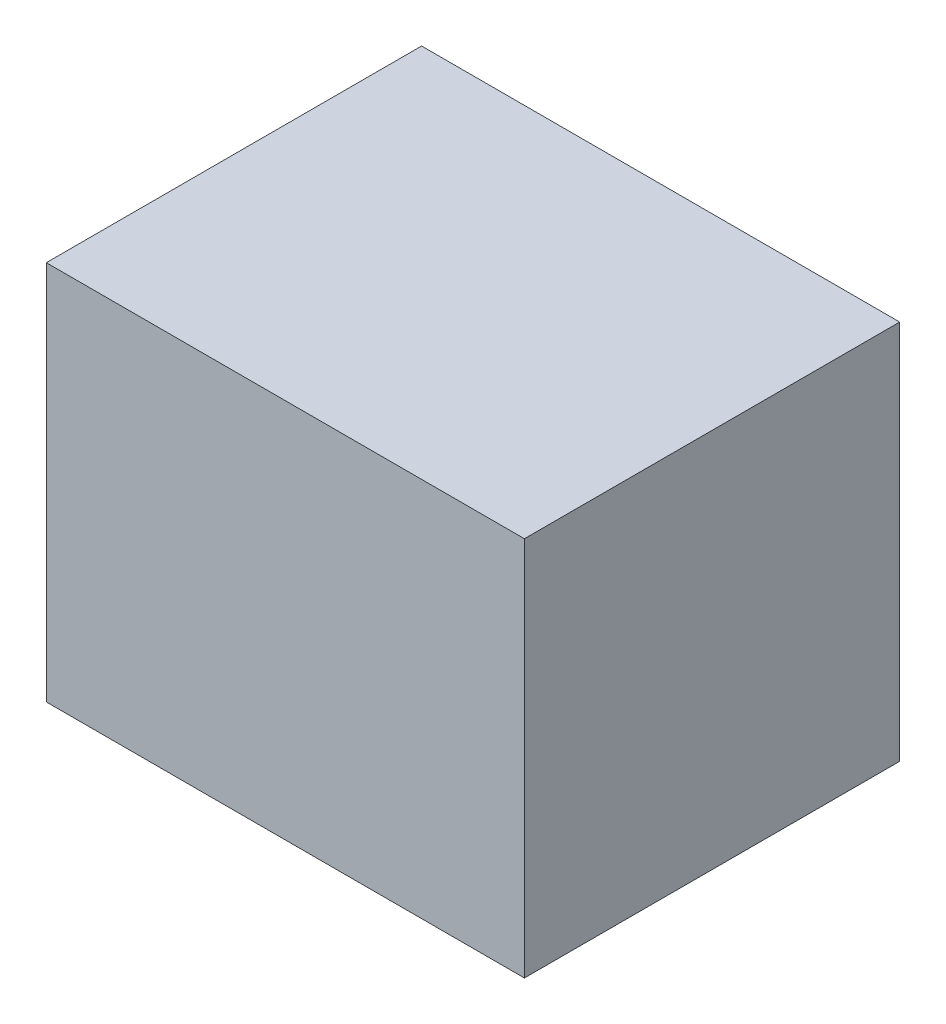
SolidWorks part; units mm, degrees
ref_plane "Front Plane" through (0, 0, 0) normal (0, 0, 1) x (1, 0, 0)
ref_plane "Top Plane" through (0, 0, 0) normal (0, 1, 0) x (1, 0, 0)
ref_plane "Right Plane" through (0, 0, 0) normal (1, 0, 0) x (0, 0, -1)
sketch "Sketch1" plane through (0, 0, 0) normal (0, 0, 1) x (1, 0, 0)
  line L1 (-46.5, -37) -> (46.5, -37)
  line L2 (-46.5, -37) -> (-46.5, 37)
  line L3 (-46.5, 37) -> (46.5, 37)
  line L4 (46.5, -37) -> (46.5, 37)
  line L5 (-46.5, -37) -> (46.5, 37) construction
  line L6 (-46.5, 37) -> (46.5, -37) construction
  point P0 (0, 0)
  dimension "D1" = 74
  dimension "D2" = 93
extrude "Boss-Extrude1" add sketch "Sketch1" along normal mid plane 73
